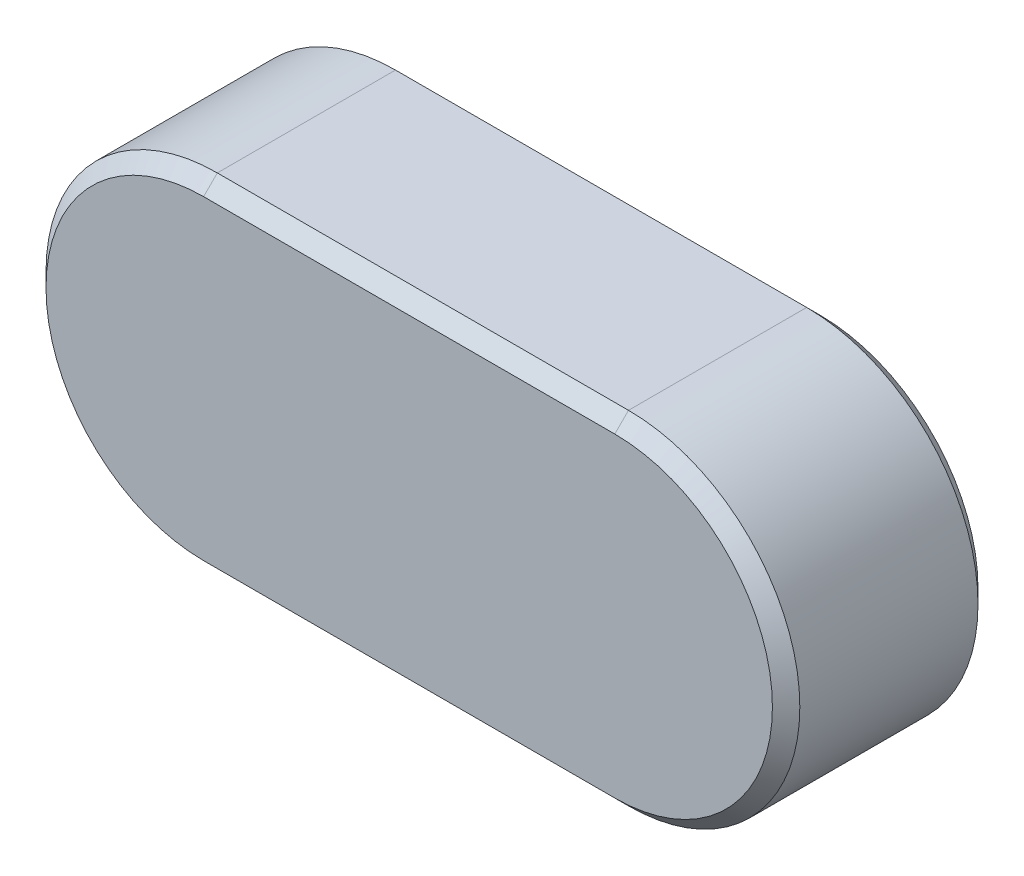
SolidWorks part; units mm, degrees
ref_plane "Front" through (0, 0, 0) normal (0, 0, 1) x (1, 0, 0)
ref_plane "Top" through (0, 0, 0) normal (0, 1, 0) x (1, 0, 0)
ref_plane "Right" through (0, 0, 0) normal (1, 0, 0) x (0, 0, -1)
sketch "Sketch1" plane through (0, 0, 0) normal (0, 0, 1) x (1, 0, 0)
  line L0 (0, 5) -> (-12, 5)
  line L1 (-12, -5) -> (0, -5)
  arc A0 (-12, 5) -> (-12, -5) centre (-12, 0) ccw
  arc A1 (0, -5) -> (0, 5) centre (0, 0) ccw
  dimension "b" = 10
  dimension "l" = 22
extrude "Extrude1" add sketch "Sketch1" along normal blind 6
sketch "Sketch2" plane through (0, 0, 0) normal (0, 0, 1) x (1, 0, 0)
  line L0 (0, 5) -> (-12, 5) construction
  line L1 (-17, 5) -> (5, 5)
  line L2 (-17, 5) -> (-17, -5)
  line L3 (-17, -5) -> (5, -5)
  line L4 (5, 5) -> (5, -5)
  line L5 (-12, -5) -> (0, -5) construction
  arc A0 (-12, 5) -> (-12, -5) centre (-12, 0) ccw construction
  arc A1 (0, -5) -> (0, 5) centre (0, 0) ccw construction
extrude "Extrude2" [suppressed] add sketch "Sketch2" along normal blind 6
sketch "Sketch3" plane through (0, 0, 0) normal (0, 0, 1) x (1, 0, 0)
  line L0 (-12, -5) -> (0, -5) construction
  line L1 (-12, -5) -> (5, -5)
  line L3 (-12, 5) -> (5, 5)
  line L4 (5, -5) -> (5, 5)
  arc A1 (-12, 5) -> (-12, -5) centre (-12, 0) ccw
  arc A2 (0, -5) -> (0, 5) centre (0, 0) ccw construction
  arc A3 (-12, 5) -> (-12, -5) centre (-12, 0) ccw construction
extrude "Extrude3" [suppressed] add sketch "Sketch3" along normal blind 6
chamfer "Chamfer1" distance 0.4 angle 45 8 edges at (-6, 5, 0) (-6, -5, 0) (-6, 5, 6) (-6, -5, 6) (-17, 0, 0) (-17, 0, 6) (5, 0, 0) (5, 0, 6)
equation "\"D1@Extrude2\" = \"h@Extrude1\""
equation "\"D1@Extrude3\" = \"h@Extrude1\""
